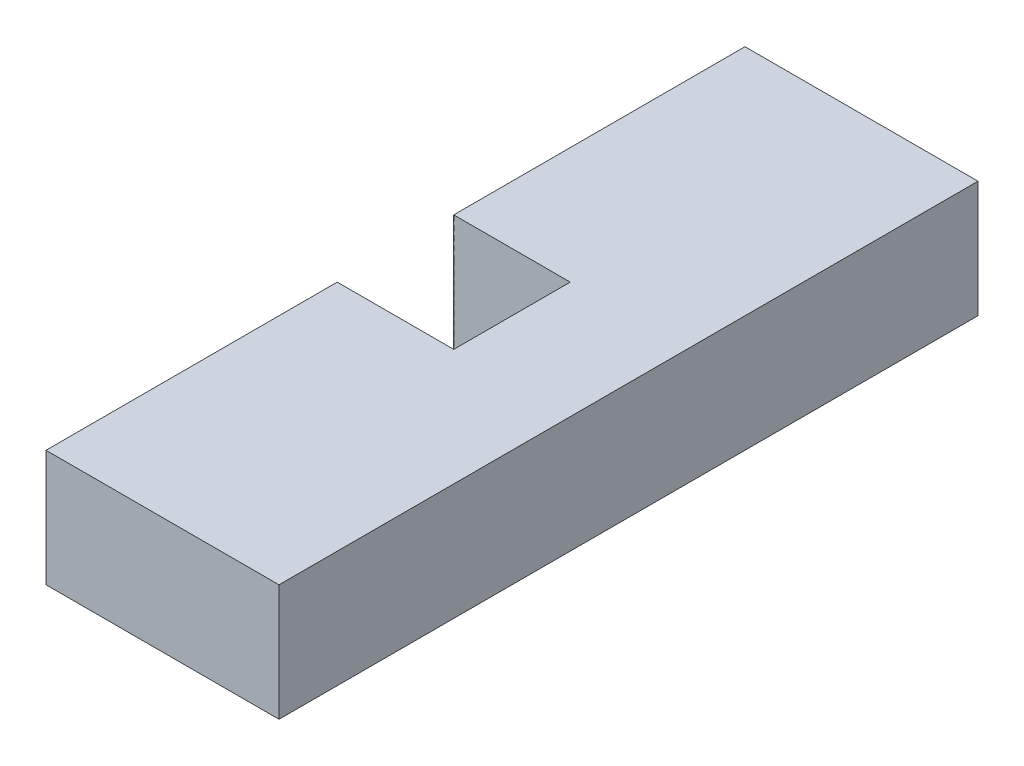
SolidWorks part; units mm, degrees
ref_plane "Front Plane" through (0, 0, 0) normal (0, 0, 1) x (1, 0, 0)
ref_plane "Top Plane" through (0, 0, 0) normal (0, 1, 0) x (1, 0, 0)
ref_plane "Right Plane" through (0, 0, 0) normal (1, 0, 0) x (0, 0, -1)
sketch "Sketch1" plane through (0, 0, 0) normal (0, 1, 0) x (1, 0, 0)
  line L1 (-6.35, 19.05) -> (6.35, 19.05)
  line L2 (-6.35, 19.05) -> (-6.35, -19.05)
  line L3 (-6.35, -19.05) -> (6.35, -19.05)
  line L4 (6.35, 19.05) -> (6.35, -19.05)
  line L5 (-6.35, 19.05) -> (6.35, -19.05) construction
  line L6 (-6.35, -19.05) -> (6.35, 19.05) construction
  point P0 (0, 0)
  dimension "D1" = 38.1
  dimension "D2" = 12.7
extrude "Boss-Extrude1" add sketch "Sketch1" along normal blind 6.35
sketch "Sketch2" plane through (0, 6.35, 0) normal (0, 1, 0) x (1, 0, 0)
  line L0 (-6.35, 19.05) -> (-6.35, -19.05) construction
  line L1 (0, 3.175) -> (-12.7, 3.175)
  line L2 (0, 3.175) -> (0, -3.175)
  line L3 (0, -3.175) -> (-12.7, -3.175)
  line L4 (-12.7, 3.175) -> (-12.7, -3.175)
  line L5 (0, 3.175) -> (-12.7, -3.175) construction
  line L6 (0, -3.175) -> (-12.7, 3.175) construction
  point P0 (-6.35, 0)
  dimension "D1" = 6.35
  dimension "D2" = 12.7
extrude "Cut-Extrude1" cut sketch "Sketch2" against normal through all
